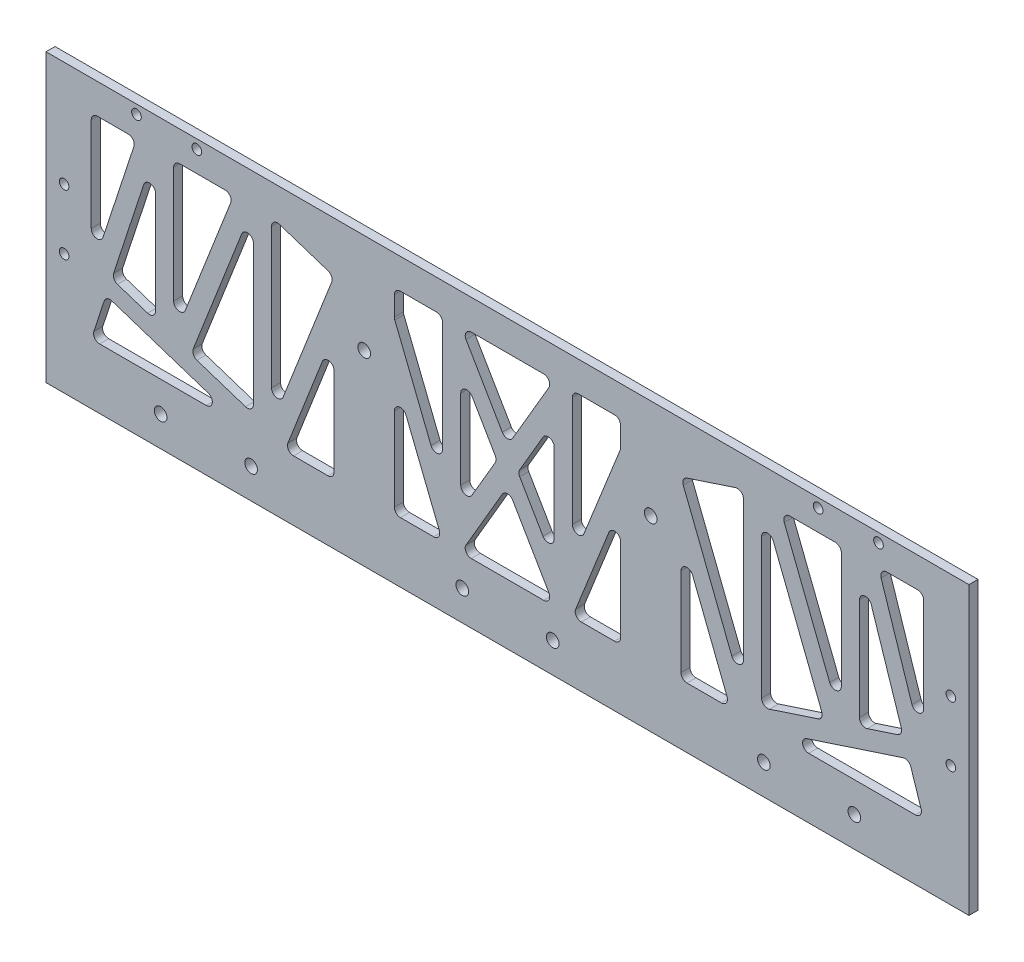
SolidWorks part; units mm, degrees
material "环氧树脂FR-4"
ref_plane "前视基准面" through (0, 0, 0) normal (0, 0, 1) x (1, 0, 0)
ref_plane "上视基准面" through (0, 0, 0) normal (0, 1, 0) x (1, 0, 0)
ref_plane "右视基准面" through (0, 0, 0) normal (1, 0, 0) x (0, 0, -1)
sketch "草图1" plane through (0, 0, 0) normal (0, 0, 1) x (1, 0, 0)
  line L1 (-153, 95) -> (153, 95)
  line L2 (-153, 95) -> (-153, 0)
  line L4 (153, 95) -> (153, 0)
  line L7 (-153, 0) -> (153, 0)
  dimension "D1" = 95
  dimension "D2" = 153
  dimension "D4" = 95
  dimension "D5" = 306
extrude "凸台-拉伸1" add sketch "草图1" along normal blind 3
sketch "草图2" plane through (0, 0, 3) normal (0, 0, 1) x (1, 0, 0)
  line L0 (-153, 0) -> (153, 0) construction
  point P0 (-47.5, 62)
  point P1 (47.5, 62)
  dimension "D1" = 62
  dimension "D2" = 62
  dimension "D3" = 95
  dimension "D4" = 47.5
hole_wizard "Ø4.2 (4.2) 直径孔1" positions "3D草图1" profile "草图3" hole size "Ø4.2" standard "GB" end condition through all
sketch3d "3D草图1"
  point P0 (-47.5, 62, 3)
  point P3 (47.5, 62, 3)
sketch "草图3" plane through (-47.5, 62, 3) normal (1, 0, 0) x (0, -1, 0)
  line L0 (0, 0) -> (0, 3)
  line L1 (0, 3) -> (2.1, 3)
  line L2 (2.1, 3) -> (2.1, 0)
  line L5 (2.1, 0) -> (0, 0)
  line L11 (0, -6.35) -> (0, 107.95) construction
  dimension "通孔孔直径" = 4.2
  dimension "通孔孔深度" = 3
sketch "草图4" plane through (0, 0, 3) normal (0, 0, 1) x (1, 0, 0)
  line L0 (-138, 20) -> (-133.0813, 35)
  line L1 (-133.0813, 35) -> (-87.3375, 20)
  line L2 (-138, 95) -> (-138, 0)
  line L3 (-138, 85) -> (-138, 39.2562)
  line L4 (-123, 85) -> (-138, 85)
  line L7 (-131.2118, 40.7013) -> (-116.6857, 85)
  line L8 (-131.2118, 40.7013) -> (-116.6857, 35.938)
  line L9 (-153, 0) -> (153, 0) construction
  line L10 (-138, 20) -> (-87.3375, 20)
  line L12 (153, 95) -> (-153, 95) construction
  line L14 (-138, 39.2562) -> (-123, 85)
  line L15 (-116.6857, 85) -> (-116.6857, 35.938)
  line L16 (-110.6857, 85) -> (-110.6857, 33.9705)
  line L17 (-104.9752, 32.098) -> (-84.2413, 25.2991)
  line L18 (-110.6857, 33.9705) -> (-90.6857, 85)
  line L19 (-104.9752, 32.098) -> (-84.2413, 85)
  line L20 (-90.6857, 85) -> (-110.6857, 85)
  line L26 (-84.2413, 85) -> (-84.2413, 25.2991)
  line L32 (-78.2413, 85) -> (-78.2413, 25.2991)
  line L33 (-78.2413, 85) -> (-57.5074, 78.2011)
  line L34 (-78.2413, 25.2991) -> (-57.5074, 78.2011)
  line L35 (-47.5, 95) -> (-47.5, 0) construction
  line L36 (-57.5, 61.7773) -> (-57.5, 20)
  line L38 (-73.8738, 20) -> (-57.5, 20)
  line L39 (-57.5, 61.7773) -> (-73.8738, 20)
  line L41 (-57.5, 95) -> (-57.5, 0) construction
  point P0 (-125, 95)
  point P1 (-125, 0)
  point P7 (-53.5037, 85)
  point P26 (-55.487, 20)
  point P27 (-78.8983, 85)
  point P28 (-47.9397, 20)
  dimension "D6" = 0
  dimension "D5" = 15
  dimension "D7" = 15
  dimension "D8" = 6
  dimension "D9" = 6
  dimension "D10" = 6
  dimension "D11" = 0
  dimension "D12" = 20
  dimension "D13" = 6
  dimension "D14" = 6
  dimension "D15" = 0
  dimension "D2" = 20
  dimension "D17" = 10
  dimension "D19" = 6
  dimension "D20" = 0
  dimension "D3" = 10
  dimension "D4" = 10
  dimension "D1" = 15
  dimension "D16" = 6
extrude "切除-拉伸1" cut sketch "草图4" against normal through all
fillet "圆角2" radius 2 21 edges at (-138, 20, 1.5) (-87.3375, 20, 1.5) (-133.0813, 35, 1.5) (-57.5, 61.7773, 1.5) (-57.5, 20, 1.5) (-73.8738, 20, 1.5) (-78.2413, 25.2991, 1.5) (-84.2413, 25.2991, 1.5) (-104.9752, 32.098, 1.5) (-110.6857, 33.9705, 1.5) (-116.6857, 35.938, 1.5) (-131.2118, 40.7013, 1.5) (-138, 39.2562, 1.5) (-57.5074, 78.2011, 1.5) (-78.2413, 85, 1.5) (-84.2413, 85, 1.5) (-90.6857, 85, 1.5) (-110.6857, 85, 1.5) (-116.6857, 85, 1.5) (-138, 85, 1.5) (-123, 85, 1.5)
mirror "镜向1" about plane through (0, 0, 0) normal (1, 0, 0) of "切除-拉伸1", "圆角2"
sketch "草图5" plane through (0, 0, 3) normal (0, 0, 1) x (1, 0, 0)
  line L0 (-15.5, 73.0994) -> (-15.5, 31.9006)
  line L1 (-37.5, 85) -> (-37.5, 76.1555)
  line L2 (-57.5, 22) -> (-57.5, 51.1934) construction
  line L3 (-37.5, 20) -> (-21.5, 20)
  line L4 (-21.5, 20) -> (-37.5, 60)
  line L5 (-93.6176, 85) -> (-108.6857, 85) construction
  line L6 (-37.5, 76.1555) -> (-21.5, 36.1555)
  line L7 (-153, 0) -> (153, 0) construction
  line L8 (-37.5, 60) -> (-37.5, 20)
  line L9 (-37.5, 85) -> (-21.5, 85)
  line L10 (-15.5, 20) -> (15.5, 20)
  line L11 (-21.5, 85) -> (-21.5, 36.1555)
  line L15 (0, -55) -> (0, 55) construction
  line L18 (21.5, 85) -> (21.5, 36.1555)
  line L19 (37.5, 85) -> (21.5, 85)
  line L20 (37.5, 60) -> (37.5, 20)
  line L21 (37.5, 76.1555) -> (21.5, 36.1555)
  line L22 (21.5, 20) -> (37.5, 60)
  line L23 (37.5, 20) -> (21.5, 20)
  line L24 (37.5, 85) -> (37.5, 76.1555)
  line L26 (15.5, 20) -> (0, 46.5497)
  line L27 (-15.5, 85) -> (15.5, 85)
  line L28 (15.5, 73.0994) -> (15.5, 31.9006)
  line L29 (15.5, 31.9006) -> (3.4738, 52.5)
  line L31 (-15.5, 20) -> (0, 46.5497)
  line L32 (-15.5, 31.9006) -> (-3.4738, 52.5)
  line L33 (-3.4738, 52.5) -> (-15.5, 73.0994)
  line L34 (3.4738, 52.5) -> (15.5, 73.0994)
  line L35 (153, 95) -> (-153, 95) construction
  line L37 (0, 58.4503) -> (15.5, 85)
  line L38 (0, 58.4503) -> (-15.5, 85)
  point P13 (-15.5, 20)
  point P19 (-12.7922, 18.7086)
  point P31 (15.5, 85)
  point P33 (18.2078, 83.7086)
  point P34 (-18.2078, 21.2914)
  point P35 (12.7922, 86.2914)
  dimension "D1" = 20
  dimension "D2" = 16
  dimension "D3" = 0
  dimension "D4" = 40
  dimension "D5" = 6
  dimension "D6" = 20
  dimension "D7" = 6
  dimension "D8" = 16
  dimension "D9" = 6
  dimension "D10" = 10
  dimension "D11" = 6
  dimension "D12" = 6
  dimension "D13" = 6
  dimension "D14" = 0
  dimension "D15" = 0
extrude "切除-拉伸2" cut sketch "草图5" against normal through all
fillet "圆角3" radius 2 26 edges at (15.5, 73.0994, 1.5) (37.5, 60, 1.5) (3.4738, 52.5, 1.5) (21.5, 20, 1.5) (21.5, 36.1555, 1.5) (15.5, 31.9006, 1.5) (37.5, 20, 1.5) (21.5, 85, 1.5) (37.5, 76.1555, 1.5) (37.5, 85, 1.5) (0, 58.4503, 1.5) (15.5, 85, 1.5) (-15.5, 85, 1.5) (-15.5, 20, 1.5) (15.5, 20, 1.5) (0, 46.5497, 1.5) (-15.5, 31.9006, 1.5) (-3.4738, 52.5, 1.5) (-15.5, 73.0994, 1.5) (-21.5, 85, 1.5) (-37.5, 85, 1.5) (-37.5, 76.1555, 1.5) (-21.5, 36.1555, 1.5) (-37.5, 60, 1.5) (-21.5, 20, 1.5) (-37.5, 20, 1.5)
sketch "草图6" plane through (0, 0, 3) normal (0, 0, 1) x (1, 0, 0)
  line L0 (-153, 0) -> (153, 0) construction
  point P0 (85, 10)
  point P4 (115, 10)
  dimension "D1" = 10
  dimension "D2" = 85
  dimension "D4" = 30
  dimension "D3" = 2
hole_wizard "Ø4.2 (4.2) 直径孔2" positions "3D草图2" profile "草图7" hole size "Ø4.2" standard "GB" end condition through all
sketch3d "3D草图2"
  point P0 (115, 10, 3)
  point P3 (85, 10, 3)
sketch "草图7" plane through (115, 10, 3) normal (1, 0, 0) x (0, -1, 0)
  line L0 (0, 0) -> (0, 3)
  line L1 (0, 3) -> (2.1, 3)
  line L2 (2.1, 3) -> (2.1, 0)
  line L5 (2.1, 0) -> (0, 0)
  line L11 (0, -6.35) -> (0, 107.95) construction
  dimension "通孔孔直径" = 4.2
  dimension "通孔孔深度" = 3
mirror "镜向2" about plane through (0, 0, 0) normal (1, 0, 0) of "Ø4.2 (4.2) 直径孔2"
sketch "草图8" plane through (0, 0, 3) normal (0, 0, 1) x (1, 0, 0)
  line L0 (-153, 0) -> (153, 0) construction
  point P0 (-15, 10)
  point P4 (15, 10)
  dimension "D1" = 10
  dimension "D2" = 15
  dimension "D4" = 30
  dimension "D3" = 2
hole_wizard "Ø4.2 (4.2) 直径孔3" positions "3D草图3" profile "草图9" hole size "Ø4.2" standard "GB" end condition through all
sketch3d "3D草图3"
  point P0 (-15, 10, 3)
  point P3 (15, 10, 3)
sketch "草图9" plane through (-15, 10, 3) normal (1, 0, 0) x (0, -1, 0)
  line L0 (0, 0) -> (0, 3)
  line L1 (0, 3) -> (2.1, 3)
  line L2 (2.1, 3) -> (2.1, 0)
  line L5 (2.1, 0) -> (0, 0)
  line L11 (0, -6.35) -> (0, 107.95) construction
  dimension "通孔孔直径" = 4.2
  dimension "通孔孔深度" = 3
sketch "草图10" plane through (0, 0, 3) normal (0, 0, 1) x (1, 0, 0)
  line L0 (153, 0) -> (153, 95) construction
  line L1 (-153, 0) -> (153, 0) construction
  point P0 (147, 40)
  point P7 (147, 60)
  dimension "D1" = 6
  dimension "D2" = 40
  dimension "D4" = 20
  dimension "D3" = 2
hole_wizard "Ø3.2 (3.2) 直径孔1" positions "3D草图4" profile "草图11" hole size "Ø3.2" standard "GB" end condition through all
sketch3d "3D草图4"
  point P0 (147, 60, 3)
  point P3 (147, 40, 3)
sketch "草图11" plane through (147, 60, 3) normal (1, 0, 0) x (0, -1, 0)
  line L0 (0, 0) -> (0, 3)
  line L1 (0, 3) -> (1.6, 3)
  line L2 (1.6, 3) -> (1.6, 0)
  line L5 (1.6, 0) -> (0, 0)
  line L11 (0, -6.35) -> (0, 107.95) construction
  dimension "通孔孔直径" = 3.2
  dimension "通孔孔深度" = 3
mirror "镜向3" about plane through (0, 0, 0) normal (1, 0, 0) of "Ø3.2 (3.2) 直径孔1"
sketch "草图12" plane through (0, 0, 3) normal (0, 0, 1) x (1, 0, 0)
  line L0 (153, 95) -> (-153, 95) construction
  line L1 (-153, 95) -> (-153, 0) construction
  point P0 (-123, 92)
  point P5 (-103, 92)
  dimension "D1" = 3
  dimension "D2" = 30
  dimension "D4" = 20
  dimension "D3" = 2
hole_wizard "Ø3.2 (3.2) 直径孔2" positions "3D草图5" profile "草图13" hole size "Ø3.2" standard "GB" end condition through all
sketch3d "3D草图5"
  point P0 (-123, 92, 3)
  point P3 (-103, 92, 3)
sketch "草图13" plane through (-123, 92, 3) normal (1, 0, 0) x (0, -1, 0)
  line L0 (0, 0) -> (0, 3)
  line L1 (0, 3) -> (1.6, 3)
  line L2 (1.6, 3) -> (1.6, 0)
  line L5 (1.6, 0) -> (0, 0)
  line L11 (0, -6.35) -> (0, 107.95) construction
  dimension "通孔孔直径" = 3.2
  dimension "通孔孔深度" = 3
mirror "镜向4" about plane through (0, 0, 0) normal (1, 0, 0) of "Ø3.2 (3.2) 直径孔2"
